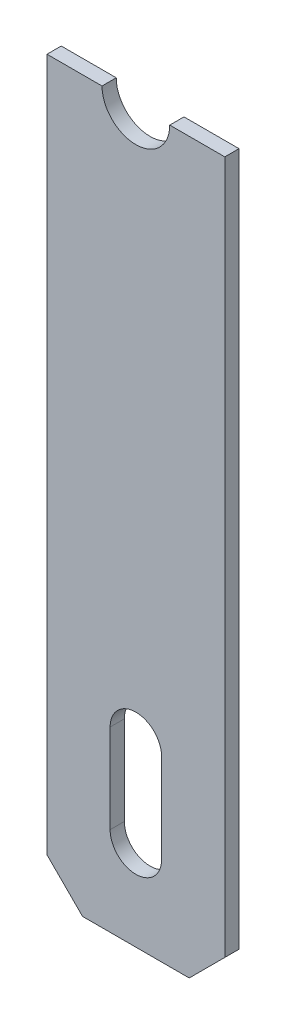
SolidWorks part; units mm, degrees
ref_plane "Front Plane" through (0, 0, 0) normal (0, 0, 1) x (1, 0, 0)
ref_plane "Top Plane" through (0, 0, 0) normal (0, 1, 0) x (1, 0, 0)
ref_plane "Right Plane" through (0, 0, 0) normal (1, 0, 0) x (0, 0, -1)
sketch "Sketch1" plane through (0, 0, 0) normal (0, 0, 1) x (1, 0, 0)
  line L0 (0, 90) -> (0, -90) construction
  line L1 (0, -90) -> (0, -65) construction
  line L2 (-7.25, -90) -> (-7.25, -65)
  line L3 (7.25, -90) -> (7.25, -65)
  line L9 (-25, -65) -> (-25, 90)
  line L16 (-25, -65) -> (-25, -105)
  line L17 (-15, -115) -> (15, -115)
  line L18 (25, -65) -> (25, -105)
  line L19 (-25, -65) -> (25, -115) construction
  line L20 (-25, -115) -> (25, -65) construction
  line L21 (-25, 90) -> (-9.525, 90)
  line L22 (9.525, 90) -> (25, 90)
  line L23 (25, 90) -> (25, -65)
  line L24 (-25, -105) -> (-15, -115)
  line L25 (15, -115) -> (25, -105)
  arc A0 (-7.25, -90) -> (7.25, -90) centre (0, -90) ccw
  arc A1 (7.25, -65) -> (-7.25, -65) centre (0, -65) ccw
  arc A3 (-9.525, 90) -> (9.525, 90) centre (0, 90) ccw
  point P0 (0, -77.5)
  point P4 (0, 0)
  point P10 (0, -90)
  point P12 (0, -90)
  dimension "D2" = 7.25
  dimension "D5" = 50
  dimension "D8" = 25
  dimension "D3" = 19.05
  dimension "D1" = 180
  dimension "D4" = 50
  dimension "D6" = 195
extrude "Boss-Extrude1" add sketch "Sketch1" along normal blind 4
